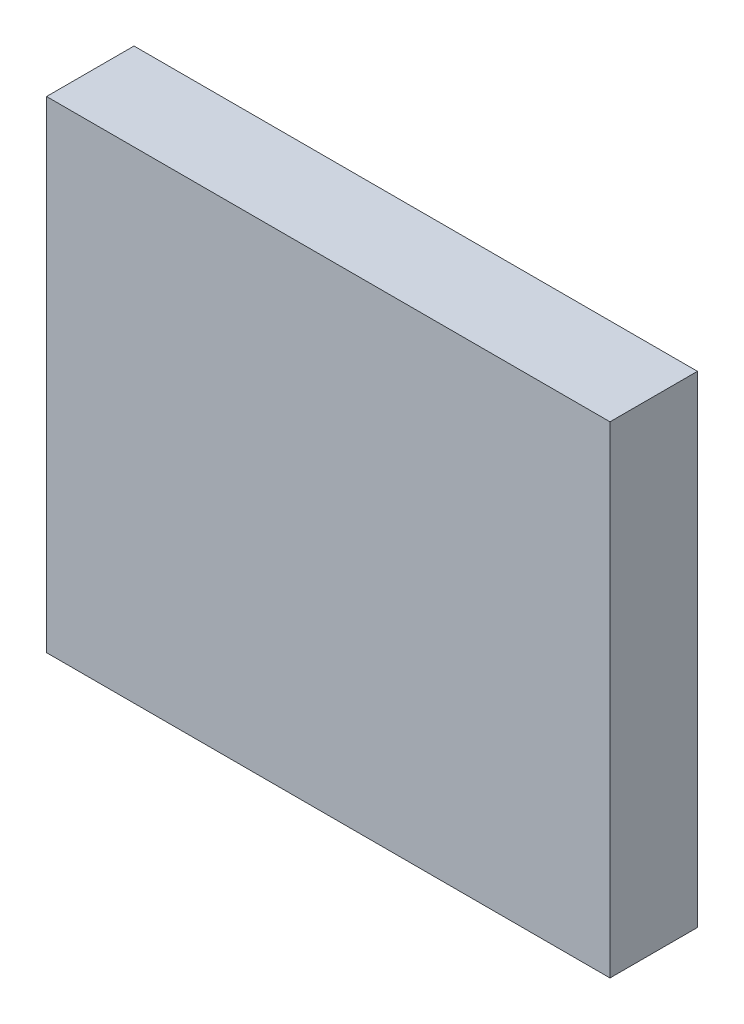
SolidWorks part; units mm, degrees
ref_plane "Front" through (0, 0, 0) normal (0, 0, 1) x (1, 0, 0)
ref_plane "Top" through (0, 0, 0) normal (0, 1, 0) x (1, 0, 0)
ref_plane "Right" through (0, 0, 0) normal (1, 0, 0) x (0, 0, -1)
sketch "Sketch1" plane through (0, 0, 0) normal (0, 0, 1) x (1, 0, 0)
  line L1 (-37.4404, 25.3679) -> (26.9806, 25.3679)
  line L2 (-37.4404, 25.3679) -> (-37.4404, -29.7071)
  line L3 (-37.4404, -29.7071) -> (26.9806, -29.7071)
  line L4 (26.9806, 25.3679) -> (26.9806, -29.7071)
extrude "Extrude1" add sketch "Sketch1" along normal blind 10
